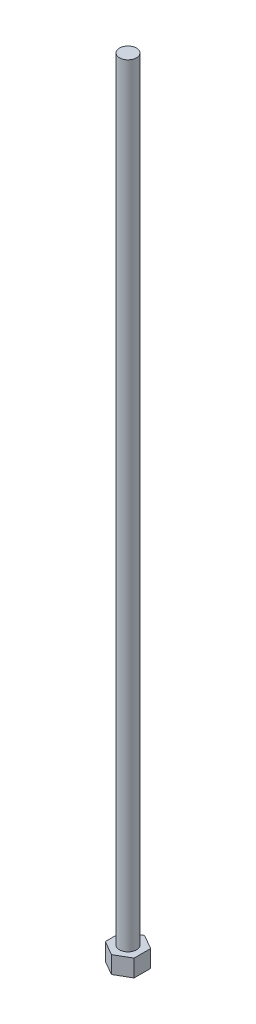
SolidWorks part; units mm, degrees
ref_plane "Front Plane" through (0, 0, 0) normal (0, 0, 1) x (1, 0, 0)
ref_plane "Top Plane" through (0, 0, 0) normal (0, 1, 0) x (1, 0, 0)
ref_plane "Right Plane" through (0, 0, 0) normal (1, 0, 0) x (0, 0, -1)
sketch "Sketch1" plane through (0, 0, 0) normal (0, 1, 0) x (1, 0, 0)
  line L1 (0, 5.7735) -> (-5, 2.8868)
  line L2 (-5, 2.8868) -> (-5, -2.8868)
  line L3 (-5, -2.8868) -> (0, -5.7735)
  line L4 (0, -5.7735) -> (5, -2.8868)
  line L5 (5, -2.8868) -> (5, 2.8868)
  line L6 (5, 2.8868) -> (0, 5.7735)
  circle A0 centre (0, 0) radius 5 construction
  point P1 (4.9836, -2.9149)
  dimension "D1" = 10
extrude "Boss-Extrude1" add sketch "Sketch1" along normal blind 6
sketch "Sketch2" plane through (0, 6, 0) normal (0, 1, 0) x (1, 0, 0)
  circle A0 centre (0, 0) radius 2.95
  dimension "D1" = 5.9
extrude "Boss-Extrude2" add sketch "Sketch2" along normal blind 269
sketch3d "3DSketch1"
  circle A0 centre (0, 274, 0) radius 2.95
  circle A1 centre (0, 274, 0) radius 2.95
  point P2 (0, 276.95, 0)
  point P4 (0, 276.95, 0)
  dimension "D1" = 1
